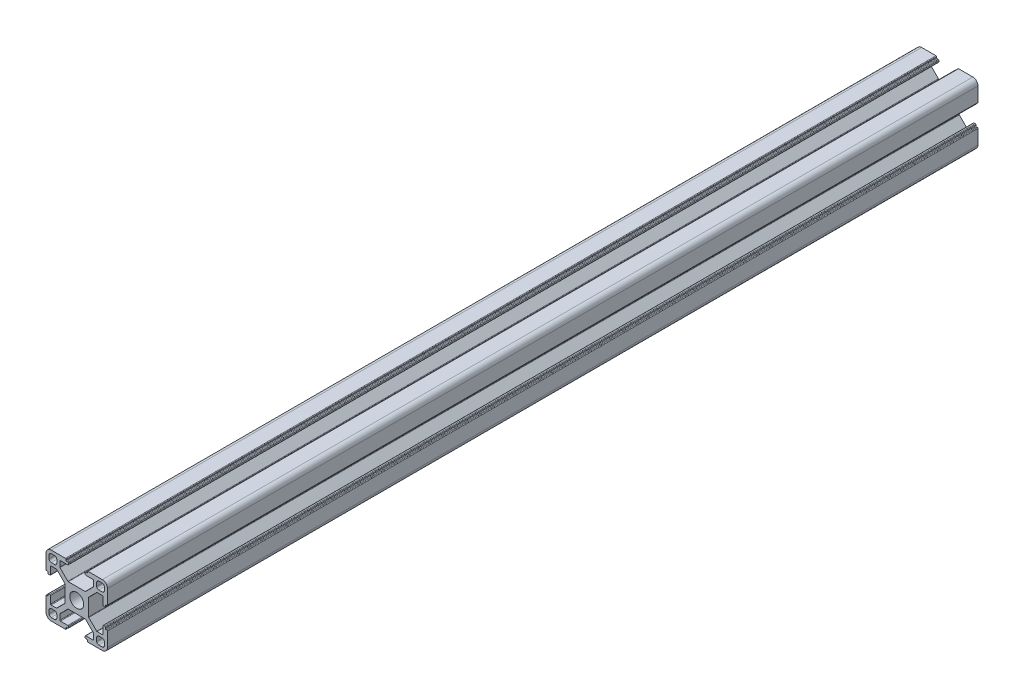
SolidWorks part; units mm, degrees
ref_plane "Front Plane" through (0, 0, 0) normal (0, 0, 1) x (1, 0, 0)
ref_plane "Top Plane" through (0, 0, 0) normal (0, 1, 0) x (1, 0, 0)
ref_plane "Right Plane" through (0, 0, 0) normal (1, 0, 0) x (0, 0, -1)
sketch "Model" plane through (0, 0, 0) normal (0, 0, 1) x (1, 0, 0)
  line L0 (21.5, 27) -> (25, 27)
  line L1 (27, 25) -> (27, 21.5)
  line L2 (25, 19.5) -> (21.5, 19.5)
  line L3 (19.5, 21.5) -> (19.5, 25)
  line L4 (21.5, -27) -> (25, -27)
  line L5 (27, -25) -> (27, -21.5)
  line L6 (25, -19.5) -> (21.5, -19.5)
  line L7 (19.5, -21.5) -> (19.5, -25)
  line L8 (0, 11.6) -> (-8.2402, 11.6)
  line L9 (-8.6645, 11.7757) -> (-16.3243, 19.4355)
  line L10 (-16.5, 19.8598) -> (-16.5, 25)
  line L11 (-15.9, 25.6) -> (-8.8, 25.6)
  line L12 (-8.2, 26.2) -> (-8.2, 27.4)
  line L13 (-8.8, 28) -> (-9.8, 28)
  line L14 (-10.4, 28.6) -> (-10.4, 29.4)
  line L15 (-11, 30) -> (-25, 30)
  line L16 (-30, 25) -> (-30, 11)
  line L17 (-29.4, 10.4) -> (-28.6, 10.4)
  line L18 (-28, 9.8) -> (-28, 8.8)
  line L19 (-27.4, 8.2) -> (-26.2, 8.2)
  line L20 (-25.6, 8.8) -> (-25.6, 15.9)
  line L21 (-25, 16.5) -> (-19.8598, 16.5)
  line L22 (-19.4355, 16.3243) -> (-11.7757, 8.6645)
  line L23 (-11.6, 8.2402) -> (-11.6, 0)
  line L24 (-11.6, 0) -> (-11.6, -8.2402)
  line L25 (-11.7757, -8.6645) -> (-19.4355, -16.3243)
  line L26 (-19.8598, -16.5) -> (-25, -16.5)
  line L27 (-25.6, -15.9) -> (-25.6, -8.8)
  line L28 (-26.2, -8.2) -> (-27.4, -8.2)
  line L29 (-28, -8.8) -> (-28, -9.8)
  line L30 (-28.6, -10.4) -> (-29.4, -10.4)
  line L31 (-30, -11) -> (-30, -25)
  line L32 (-25, -30) -> (-11, -30)
  line L33 (-10.4, -29.4) -> (-10.4, -28.6)
  line L34 (-9.8, -28) -> (-8.8, -28)
  line L35 (-8.2, -27.4) -> (-8.2, -26.2)
  line L36 (-8.8, -25.6) -> (-15.9, -25.6)
  line L37 (-16.5, -25) -> (-16.5, -19.8598)
  line L38 (-16.3243, -19.4355) -> (-8.6645, -11.7757)
  line L39 (-8.2402, -11.6) -> (0, -11.6)
  line L40 (0, -11.6) -> (8.2402, -11.6)
  line L41 (8.6645, -11.7757) -> (16.3243, -19.4355)
  line L42 (16.5, -19.8598) -> (16.5, -25)
  line L43 (15.9, -25.6) -> (8.8, -25.6)
  line L44 (8.2, -26.2) -> (8.2, -27.4)
  line L45 (8.8, -28) -> (9.8, -28)
  line L46 (10.4, -28.6) -> (10.4, -29.4)
  line L47 (11, -30) -> (25, -30)
  line L48 (30, -25) -> (30, -11)
  line L49 (29.4, -10.4) -> (28.6, -10.4)
  line L50 (28, -9.8) -> (28, -8.8)
  line L51 (27.4, -8.2) -> (26.2, -8.2)
  line L52 (25.6, -8.8) -> (25.6, -15.9)
  line L53 (25, -16.5) -> (19.8598, -16.5)
  line L54 (19.4355, -16.3243) -> (11.7757, -8.6645)
  line L55 (11.6, -8.2402) -> (11.6, 0)
  line L56 (11.6, 0) -> (11.6, 8.2402)
  line L57 (11.7757, 8.6645) -> (19.6113, 16.5)
  line L58 (19.6113, 16.5) -> (25, 16.5)
  line L59 (25.6, 15.9) -> (25.6, 8.8)
  line L60 (26.2, 8.2) -> (27.4, 8.2)
  line L61 (28, 8.8) -> (28, 9.8)
  line L62 (28.6, 10.4) -> (29.4, 10.4)
  line L63 (30, 11) -> (30, 25)
  line L64 (25, 30) -> (11, 30)
  line L65 (10.4, 29.4) -> (10.4, 28.6)
  line L66 (9.8, 28) -> (8.8, 28)
  line L67 (8.2, 27.4) -> (8.2, 26.2)
  line L68 (8.8, 25.6) -> (15.9, 25.6)
  line L69 (16.5, 25) -> (16.5, 19.8598)
  line L70 (16.3243, 19.4355) -> (8.6645, 11.7757)
  line L71 (8.2402, 11.6) -> (0, 11.6)
  line L72 (-21.5, -27) -> (-25, -27)
  line L73 (-27, -25) -> (-27, -21.5)
  line L74 (-25, -19.5) -> (-21.5, -19.5)
  line L75 (-19.5, -21.5) -> (-19.5, -25)
  line L76 (-21.5, 27) -> (-25, 27)
  line L77 (-27, 25) -> (-27, 21.5)
  line L78 (-25, 19.5) -> (-21.5, 19.5)
  line L79 (-19.5, 21.5) -> (-19.5, 25)
  circle A0 centre (0, 0) radius 6.8
  arc A1 (21.5, 27) -> (19.5, 25) centre (21.5, 25) ccw
  arc A2 (27, 25) -> (25, 27) centre (25, 25) ccw
  arc A3 (25, 19.5) -> (27, 21.5) centre (25, 21.5) ccw
  arc A4 (19.5, 21.5) -> (21.5, 19.5) centre (21.5, 21.5) ccw
  arc A5 (19.5, -25) -> (21.5, -27) centre (21.5, -25) ccw
  arc A6 (25, -27) -> (27, -25) centre (25, -25) ccw
  arc A7 (27, -21.5) -> (25, -19.5) centre (25, -21.5) ccw
  arc A8 (21.5, -19.5) -> (19.5, -21.5) centre (21.5, -21.5) ccw
  arc A9 (-8.6645, 11.7757) -> (-8.2402, 11.6) centre (-8.2402, 12.2) ccw
  arc A10 (-16.5, 19.8598) -> (-16.3243, 19.4355) centre (-15.9, 19.8598) ccw
  arc A11 (-15.9, 25.6) -> (-16.5, 25) centre (-15.9, 25) ccw
  arc A12 (-8.8, 25.6) -> (-8.2, 26.2) centre (-8.8, 26.2) ccw
  arc A13 (-8.2, 27.4) -> (-8.8, 28) centre (-8.8, 27.4) ccw
  arc A14 (-10.4, 28.6) -> (-9.8, 28) centre (-9.8, 28.6) ccw
  arc A15 (-10.4, 29.4) -> (-11, 30) centre (-11, 29.4) ccw
  arc A16 (-25, 30) -> (-30, 25) centre (-25, 25) ccw
  arc A17 (-30, 11) -> (-29.4, 10.4) centre (-29.4, 11) ccw
  arc A18 (-28, 9.8) -> (-28.6, 10.4) centre (-28.6, 9.8) ccw
  arc A19 (-28, 8.8) -> (-27.4, 8.2) centre (-27.4, 8.8) ccw
  arc A20 (-26.2, 8.2) -> (-25.6, 8.8) centre (-26.2, 8.8) ccw
  arc A21 (-25, 16.5) -> (-25.6, 15.9) centre (-25, 15.9) ccw
  arc A22 (-19.4355, 16.3243) -> (-19.8598, 16.5) centre (-19.8598, 15.9) ccw
  arc A23 (-11.6, 8.2402) -> (-11.7757, 8.6645) centre (-12.2, 8.2402) ccw
  arc A24 (-11.7757, -8.6645) -> (-11.6, -8.2402) centre (-12.2, -8.2402) ccw
  arc A25 (-19.8598, -16.5) -> (-19.4355, -16.3243) centre (-19.8598, -15.9) ccw
  arc A26 (-25.6, -15.9) -> (-25, -16.5) centre (-25, -15.9) ccw
  arc A27 (-25.6, -8.8) -> (-26.2, -8.2) centre (-26.2, -8.8) ccw
  arc A28 (-27.4, -8.2) -> (-28, -8.8) centre (-27.4, -8.8) ccw
  arc A29 (-28.6, -10.4) -> (-28, -9.8) centre (-28.6, -9.8) ccw
  arc A30 (-29.4, -10.4) -> (-30, -11) centre (-29.4, -11) ccw
  arc A31 (-30, -25) -> (-25, -30) centre (-25, -25) ccw
  arc A32 (-11, -30) -> (-10.4, -29.4) centre (-11, -29.4) ccw
  arc A33 (-9.8, -28) -> (-10.4, -28.6) centre (-9.8, -28.6) ccw
  arc A34 (-8.8, -28) -> (-8.2, -27.4) centre (-8.8, -27.4) ccw
  arc A35 (-8.2, -26.2) -> (-8.8, -25.6) centre (-8.8, -26.2) ccw
  arc A36 (-16.5, -25) -> (-15.9, -25.6) centre (-15.9, -25) ccw
  arc A37 (-16.3243, -19.4355) -> (-16.5, -19.8598) centre (-15.9, -19.8598) ccw
  arc A38 (-8.2402, -11.6) -> (-8.6645, -11.7757) centre (-8.2402, -12.2) ccw
  arc A39 (8.6645, -11.7757) -> (8.2402, -11.6) centre (8.2402, -12.2) ccw
  arc A40 (16.5, -19.8598) -> (16.3243, -19.4355) centre (15.9, -19.8598) ccw
  arc A41 (15.9, -25.6) -> (16.5, -25) centre (15.9, -25) ccw
  arc A42 (8.8, -25.6) -> (8.2, -26.2) centre (8.8, -26.2) ccw
  arc A43 (8.2, -27.4) -> (8.8, -28) centre (8.8, -27.4) ccw
  arc A44 (10.4, -28.6) -> (9.8, -28) centre (9.8, -28.6) ccw
  arc A45 (10.4, -29.4) -> (11, -30) centre (11, -29.4) ccw
  arc A46 (25, -30) -> (30, -25) centre (25, -25) ccw
  arc A47 (30, -11) -> (29.4, -10.4) centre (29.4, -11) ccw
  arc A48 (28, -9.8) -> (28.6, -10.4) centre (28.6, -9.8) ccw
  arc A49 (28, -8.8) -> (27.4, -8.2) centre (27.4, -8.8) ccw
  arc A50 (26.2, -8.2) -> (25.6, -8.8) centre (26.2, -8.8) ccw
  arc A51 (25, -16.5) -> (25.6, -15.9) centre (25, -15.9) ccw
  arc A52 (19.4355, -16.3243) -> (19.8598, -16.5) centre (19.8598, -15.9) ccw
  arc A53 (11.6, -8.2402) -> (11.7757, -8.6645) centre (12.2, -8.2402) ccw
  arc A54 (11.7757, 8.6645) -> (11.6, 8.2402) centre (12.2, 8.2402) ccw
  arc A55 (25.6, 15.9) -> (25, 16.5) centre (25, 15.9) ccw
  arc A56 (25.6, 8.8) -> (26.2, 8.2) centre (26.2, 8.8) ccw
  arc A57 (27.4, 8.2) -> (28, 8.8) centre (27.4, 8.8) ccw
  arc A58 (28.6, 10.4) -> (28, 9.8) centre (28.6, 9.8) ccw
  arc A59 (29.4, 10.4) -> (30, 11) centre (29.4, 11) ccw
  arc A60 (30, 25) -> (25, 30) centre (25, 25) ccw
  arc A61 (11, 30) -> (10.4, 29.4) centre (11, 29.4) ccw
  arc A62 (9.8, 28) -> (10.4, 28.6) centre (9.8, 28.6) ccw
  arc A63 (8.8, 28) -> (8.2, 27.4) centre (8.8, 27.4) ccw
  arc A64 (8.2, 26.2) -> (8.8, 25.6) centre (8.8, 26.2) ccw
  arc A65 (16.5, 25) -> (15.9, 25.6) centre (15.9, 25) ccw
  arc A66 (16.3243, 19.4355) -> (16.5, 19.8598) centre (15.9, 19.8598) ccw
  arc A67 (8.2402, 11.6) -> (8.6645, 11.7757) centre (8.2402, 12.2) ccw
  arc A68 (-21.5, -27) -> (-19.5, -25) centre (-21.5, -25) ccw
  arc A69 (-27, -25) -> (-25, -27) centre (-25, -25) ccw
  arc A70 (-25, -19.5) -> (-27, -21.5) centre (-25, -21.5) ccw
  arc A71 (-19.5, -21.5) -> (-21.5, -19.5) centre (-21.5, -21.5) ccw
  arc A72 (-19.5, 25) -> (-21.5, 27) centre (-21.5, 25) ccw
  arc A73 (-25, 27) -> (-27, 25) centre (-25, 25) ccw
  arc A74 (-27, 21.5) -> (-25, 19.5) centre (-25, 21.5) ccw
  arc A75 (-21.5, 19.5) -> (-19.5, 21.5) centre (-21.5, 21.5) ccw
extrude "Boss-Extrude1" add sketch "Model" along normal blind 850
scale "Scale1" bodies to scale 101 scale about centroid uniform scaling yes scale factor 0.5
